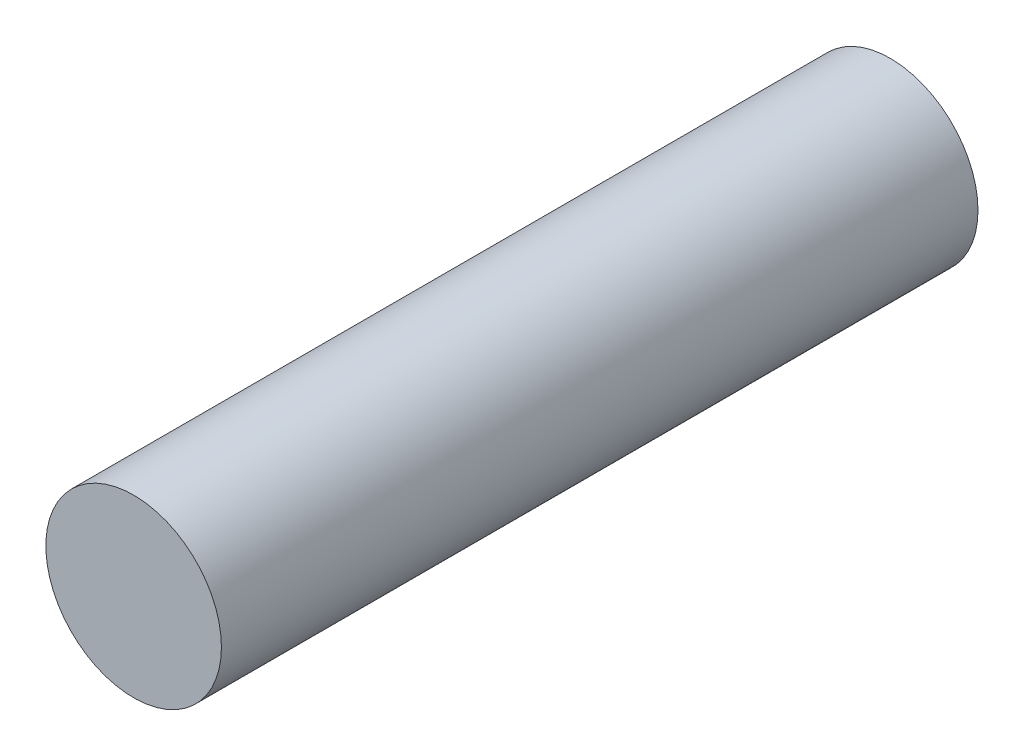
SolidWorks part; units mm, degrees
ref_plane "Front Plane" through (0, 0, 0) normal (0, 0, 1) x (1, 0, 0)
ref_plane "Top Plane" through (0, 0, 0) normal (0, 1, 0) x (1, 0, 0)
ref_plane "Right Plane" through (0, 0, 0) normal (1, 0, 0) x (0, 0, -1)
sketch "Sketch1" plane through (0, 0, 0) normal (0, 0, 1) x (1, 0, 0)
  line L0 (13.9055, 0) -> (52.0055, 0)
  line L1 (52.0055, 0) -> (52.0055, 25.4)
  line L2 (52.0055, 25.4) -> (26.6055, 76.2)
  line L3 (26.6055, 76.2) -> (13.9055, 76.2)
  line L4 (13.9055, 76.2) -> (13.9055, 63.5)
  line L8 (13.9055, 25.4) -> (13.9055, 0)
  line L9 (13.9055, 63.5) -> (22.1886, 51.6705)
  line L10 (22.1886, 51.6705) -> (22.1886, 37.2295)
  line L11 (22.1886, 37.2295) -> (13.9055, 25.4)
  line L12 (0, 0) -> (0, 106.6645) construction
  line L13 (-22.1886, 37.2295) -> (-13.9055, 25.4)
  line L14 (-22.1886, 51.6705) -> (-22.1886, 37.2295)
  line L15 (-13.9055, 63.5) -> (-22.1886, 51.6705)
  line L16 (-13.9055, 25.4) -> (-13.9055, 0)
  line L17 (-13.9055, 76.2) -> (-13.9055, 63.5)
  line L18 (-26.6055, 76.2) -> (-13.9055, 76.2)
  line L19 (-52.0055, 25.4) -> (-26.6055, 76.2)
  line L20 (-52.0055, 0) -> (-52.0055, 25.4)
  line L21 (-13.9055, 0) -> (-52.0055, 0)
  line L24 (-7.493, 16.8) -> (7.493, 16.8) construction
  line L25 (-7.493, 33.6) -> (7.493, 33.6) construction
  line L26 (-7.493, 33.6) -> (-7.493, 0) construction
  line L27 (-7.493, 0) -> (7.493, 0) construction
  line L28 (7.493, 33.6) -> (7.493, 0) construction
  line L30 (-33.493, 24.8) -> (-17.493, 24.8) construction
  line L31 (-33.493, 24.8) -> (-33.493, 8.8) construction
  line L32 (-33.493, 8.8) -> (-17.493, 8.8) construction
  line L33 (-17.493, 24.8) -> (-17.493, 8.8) construction
  line L34 (-33.493, 24.8) -> (-17.493, 8.8) construction
  line L35 (-33.493, 8.8) -> (-17.493, 24.8) construction
  line L36 (17.493, 24.8) -> (33.493, 24.8) construction
  line L37 (17.493, 24.8) -> (17.493, 8.8) construction
  line L38 (17.493, 8.8) -> (33.493, 8.8) construction
  line L39 (33.493, 24.8) -> (33.493, 8.8) construction
  line L40 (17.493, 24.8) -> (33.493, 8.8) construction
  line L41 (17.493, 8.8) -> (33.493, 24.8) construction
  circle A0 centre (-25.493, 16.8) radius 18 construction
  circle A1 centre (25.493, 16.8) radius 18 construction
  circle A2 centre (-33.493, 8.8) radius 2
  circle A3 centre (-17.493, 8.8) radius 2
  circle A4 centre (17.493, 8.8) radius 2
  circle A5 centre (33.493, 8.8) radius 2
  point P26 (0, 0)
  point P31 (-25.493, 16.8)
  point P32 (0, 16.8)
  dimension "D8" = 36
  dimension "D12" = 4
  dimension "D13" = 1.5875
  dimension "D2" = 38.1
  dimension "D3" = 25.4
  dimension "D4" = 12.7
  dimension "D5" = 38.1
  dimension "D6" = 145
  dimension "D7" = 145
  dimension "D9" = 14.986
  dimension "D10" = 33.6
  dimension "D11" = 16
extrude "Boss-Extrude1" add sketch "Sketch1" along normal mid plane 12.7 contours L10 L11 L8 L0 L1 L2 L3 L4 L9 A5 A4 | A4 | A5
sketch "Sketch2" plane through (0, 0, 0) normal (0, 0, 1) x (1, 0, 0)
  circle A0 centre (25.493, 16.8) radius 7
  dimension "D1" = 14
extrude "Cut-Extrude1" cut sketch "Sketch2" against normal through all both and the other way through all
sketch "Sketch5" plane through (0, 0, 6.35) normal (0, 0, 1) x (1, 0, 0)
  circle A0 centre (25.493, 16.8) radius 7 construction
  circle A1 centre (25.493, 16.8) radius 7
extrude "Boss-Extrude2" add sketch "Sketch5" along normal blind 47.625 and the other way up to surface (12.7 mm away) separate body other way up to face at (32.493, 16.8, -6.35)
ref_plane "Plane1" through (0, 0, 15.875) normal (0, 0, 1) x (1, 0, 0)
sketch "Sketch6" plane through (0, 0, 15.875) normal (0, 0, 1) x (1, 0, 0)
  line L0 (14.3805, 0) -> (-14.3805, 0)
  line L1 (14.3805, 30.15) -> (36.6055, 30.15)
  line L2 (14.3805, 30.15) -> (14.3805, 0)
  line L3 (14.3805, -22.225) -> (36.6055, -22.225)
  line L4 (36.6055, 30.15) -> (36.6055, -22.225)
  line L5 (36.6055, -22.225) -> (14.3805, -22.225)
  line L13 (14.3805, 0) -> (14.3805, -22.225) construction
  line L14 (25.493, 30.15) -> (25.493, -22.225) construction
  line L15 (0, 0) -> (0, -22.225)
  line L16 (-14.3805, -22.225) -> (14.3805, -22.225)
  line L17 (0, 0) -> (0, 106.6645) construction
  line L18 (0, 0) -> (0, 106.6645) construction
  line L19 (-25.493, 30.15) -> (-25.493, -22.225) construction
  line L20 (-14.3805, 0) -> (-14.3805, -22.225) construction
  line L22 (-36.6055, -22.225) -> (-14.3805, -22.225)
  line L23 (-36.6055, 30.15) -> (-36.6055, -22.225)
  line L24 (-14.3805, -22.225) -> (-36.6055, -22.225)
  line L25 (-14.3805, 30.15) -> (-14.3805, 0)
  line L26 (-14.3805, 30.15) -> (-36.6055, 30.15)
  circle A1 centre (25.493, 16.8) radius 7 construction
  circle A2 centre (25.493, 16.8) radius 7
  circle A3 centre (-25.493, 16.8) radius 7
  dimension "D2" = 6.35
  dimension "D1" = 22.225
extrude "Boss-Extrude3" add sketch "Sketch6" along normal mid plane 12.7 separate body contours L25 L26 L23 L22 L16 L15 L0 A3 | L15 L16 L3 L4 L1 L2 L0 A2
fillet "Fillet1" radius 6.35 8 edges at (-14.3805, 0, 15.875) (14.3805, 0, 15.875) (14.3805, 30.15, 15.875) (36.6055, -22.225, 15.875) (-36.6055, -22.225, 15.875) (-36.6055, 30.15, 15.875) (-14.3805, 30.15, 15.875) (36.6055, 30.15, 15.875)
fillet "Fillet2" radius 3.175 9 edges at (22.1886, 51.6705, 0) (13.9055, 63.5, 0) (13.9055, 76.2, 0) (52.0055, 25.4, 0) (52.0055, 0, 0) (13.9055, 0, 0) (13.9055, 25.4, 0) (22.1886, 37.2295, 0) (26.6055, 76.2, 0)
sketch "Sketch7" plane through (0, 0, 6.35) normal (0, 0, 1) x (1, 0, 0)
  circle A0 centre (25.493, 16.8) radius 7 construction
  circle A1 centre (25.493, 16.8) radius 7
  circle A2 centre (25.493, 16.8) radius 10.175
  dimension "D1" = 3.175
extrude "Boss-Extrude4" add sketch "Sketch7" along normal up to surface (3.175 mm away) separate body
delete or keep bodies "Body-Delete/Keep 1" type delete bodies bodies 109 111 112
